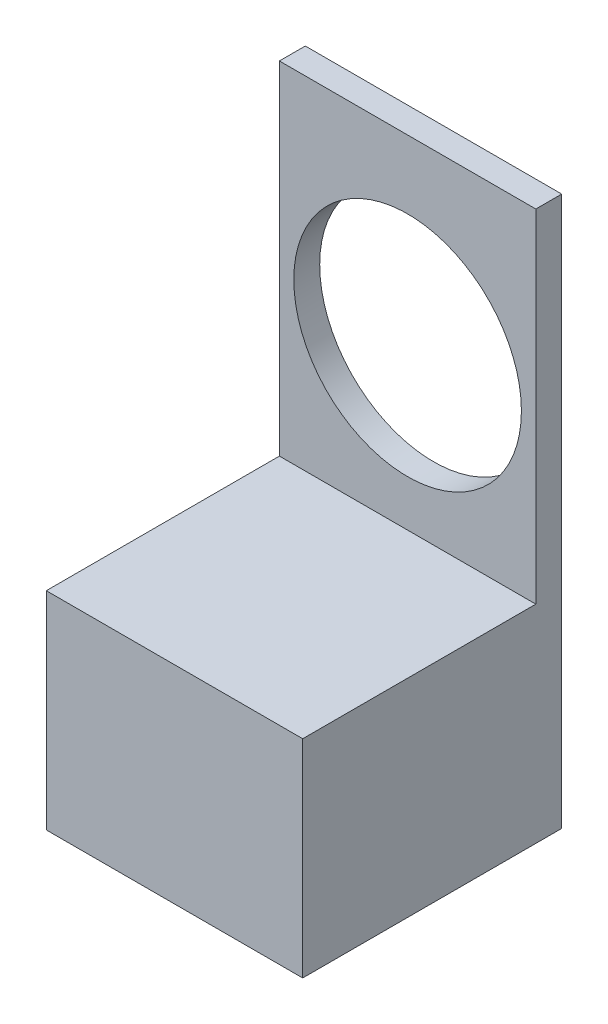
SolidWorks part; units mm, degrees
ref_plane "Front Plane" through (0, 0, 0) normal (0, 0, 1) x (1, 0, 0)
ref_plane "Top Plane" through (0, 0, 0) normal (0, 1, 0) x (1, 0, 0)
ref_plane "Right Plane" through (0, 0, 0) normal (1, 0, 0) x (0, 0, -1)
sketch "Sketch1" plane through (0, 0, 0) normal (0, 1, 0) x (1, 0, 0)
  line L1 (0, 0) -> (25.146, 0)
  line L2 (0, 0) -> (0, 22.86)
  line L3 (0, 22.86) -> (25.146, 22.86)
  line L4 (25.146, 0) -> (25.146, 22.86)
  dimension "D1" = 22.86
  dimension "D2" = 25.146
extrude "Boss-Extrude1" add sketch "Sketch1" along normal blind 20.32
sketch "Sketch2" plane through (0, 0, -22.86) normal (0, 0, -1) x (-1, 0, 0)
  line L4 (-25.146, 0) -> (0, 0)
  line L5 (0, 0) -> (0, 20.32)
  line L6 (0, 20.32) -> (-25.146, 20.32)
  line L7 (-25.146, 20.32) -> (-25.146, 0)
  line L8 (-25.146, 0) -> (0, 0)
  line L9 (0, 0) -> (0, 53.8773)
  line L10 (0, 53.8773) -> (-25.146, 53.8773)
  line L11 (-25.146, 53.8773) -> (-25.146, 0)
  dimension "D1" = 0
extrude "Boss-Extrude2" add sketch "Sketch2" along normal blind 2.54
sketch "Sketch4" plane through (0, 0, -25.4) normal (0, 0, -1) x (-1, 0, 0)
  line L0 (0, 53.8773) -> (-25.146, 53.8773) construction
  line L1 (-12.573, 53.8773) -> (-12.573, 16.5269) construction
  circle A0 centre (-12.573, 36.0171) radius 11.1598
  point P2 (0, 0)
  point P7 (-12.573, 36.0171)
extrude "Cut-Extrude1" cut sketch "Sketch4" against normal blind 2.54
